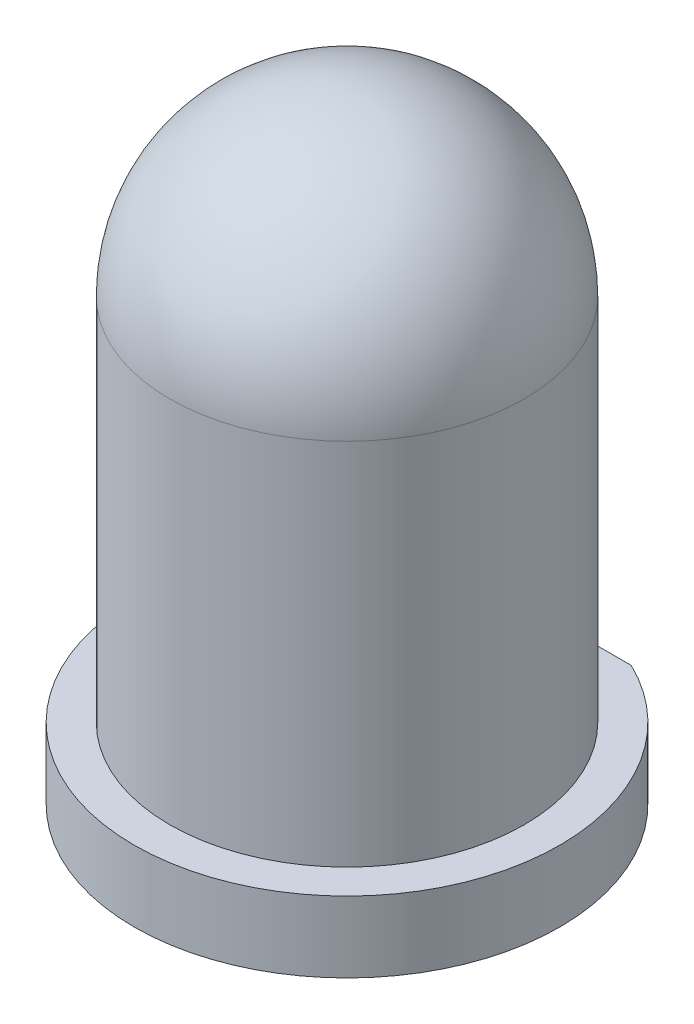
SolidWorks part; units mm, degrees
material "Acrylic (Medium-high impact)"
ref_plane "Front Plane" through (0, 0, 0) normal (0, 0, 1) x (1, 0, 0)
ref_plane "Top Plane" through (0, 0, 0) normal (0, 1, 0) x (1, 0, 0)
ref_plane "Right Plane" through (0, 0, 0) normal (1, 0, 0) x (0, 0, -1)
sketch "Sketch1" plane through (0, 0, 0) normal (0, 0, 1) x (1, 0, 0)
  line L0 (0, -0.5) -> (0, 8.2) construction
  line L1 (-3, 0.5) -> (-2.5, 0.5)
  line L2 (-3, 0.5) -> (-3, -0.5)
  line L3 (-3, -0.5) -> (3, -0.5)
  line L4 (3, 0.5) -> (3, -0.5)
  line L7 (-2.5, 0.5) -> (-2.5, 5.7)
  line L8 (2.5, 5.7) -> (2.5, 0.5)
  line L9 (2.5, 0.5) -> (3, 0.5)
  arc A0 (-2.5, 5.7) -> (2.5, 5.7) centre (0, 5.7) cw
  point P0 (0, 0)
  point P12 (0, 0)
  point P13 (0, 8.2)
  point P15 (0, 0)
  point P16 (0, -0.5)
  dimension "D2" = 2.5
  dimension "D1" = 1
  dimension "D3" = 5.2
  dimension "D4" = 6
revolve "Revolve1" add sketch "Sketch1" angle 360 about L0
ref_plane "Plane2" through (3, 0, 0) normal (1, 0, 0) x (0, 0, -1)
sketch "Sketch3" plane through (3, 0, 0) normal (1, 0, 0) x (0, 0, -1)
  line L0 (-3, -0.5) -> (3, -0.5) construction
  line L1 (3, 0.5) -> (2.7, 0.5)
  line L2 (3, 0.5) -> (3, -0.5)
  line L3 (3, -0.5) -> (2.7, -0.5)
  line L4 (2.7, 0.5) -> (2.7, -0.5)
  dimension "D1" = 0.3
extrude "Cut-Extrude1" cut sketch "Sketch3" against normal blind 10
